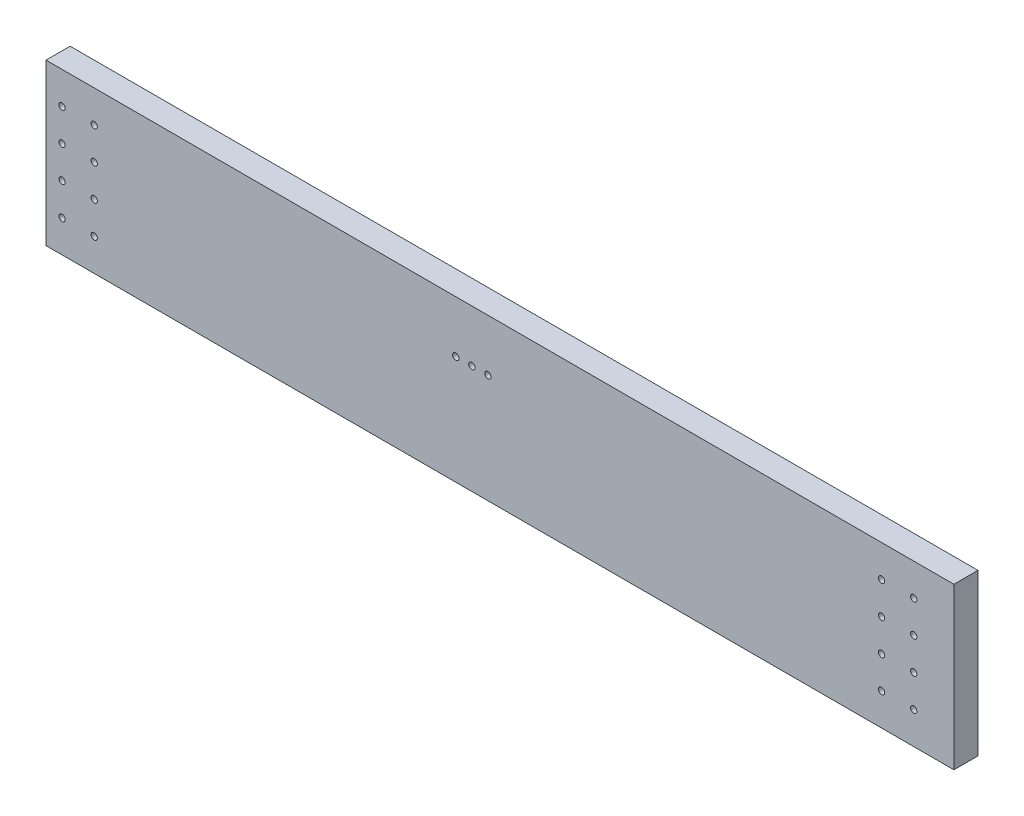
SolidWorks part; units mm, degrees
material "Pine"
ref_plane "Front Plane" through (0, 0, 0) normal (0, 0, 1) x (1, 0, 0)
ref_plane "Top Plane" through (0, 0, 0) normal (0, 1, 0) x (1, 0, 0)
ref_plane "Right Plane" through (0, 0, 0) normal (1, 0, 0) x (0, 0, -1)
sketch "Sketch1" plane through (0, 0, 0) normal (0, 0, 1) x (1, 0, 0)
  line L1 (0, 0) -> (717.55, 0)
  line L2 (0, 0) -> (0, 127)
  line L3 (0, 127) -> (717.55, 127)
  line L4 (717.55, 0) -> (717.55, 127)
  line L6 (717.55, 0) -> (717.55, 127)
  line L9 (0, 127) -> (-19.05, 127)
  line L10 (0, 127) -> (0, 0)
  line L11 (0, 0) -> (-19.05, 0)
  line L12 (-19.05, 127) -> (-19.05, 0)
  dimension "D1" = 717.55
  dimension "D2" = 127
  dimension "D3" = 19.05
extrude "Boss-Extrude1" add sketch "Sketch1" along normal blind 19.05 contours L1 L4 L3 L2
sketch "Sketch2" plane through (0, 0, 19.05) normal (0, 0, 1) x (1, 0, 0)
  line L3 (0, 0) -> (0, 127) construction
  line L4 (0, 127) -> (717.55, 127) construction
  line L5 (717.55, 0) -> (717.55, 127) construction
  circle A0 centre (12.7, 101.6) radius 2.4892
  circle A1 centre (38.1, 101.6) radius 2.4892
  circle A2 centre (38.1, 76.2) radius 2.4892
  circle A3 centre (38.1, 50.8) radius 2.4892
  circle A4 centre (38.1, 25.4) radius 2.4892
  circle A5 centre (12.7, 76.2) radius 2.4892
  circle A6 centre (12.7, 50.8) radius 2.4892
  circle A7 centre (12.7, 25.4) radius 2.4892
  circle A8 centre (685.8, 101.6) radius 2.4892
  circle A9 centre (660.4, 101.6) radius 2.4892
  circle A10 centre (660.4, 76.2) radius 2.4892
  circle A11 centre (660.4, 50.8) radius 2.4892
  circle A12 centre (660.4, 25.4) radius 2.4892
  circle A13 centre (685.8, 76.2) radius 2.4892
  circle A14 centre (685.8, 50.8) radius 2.4892
  circle A15 centre (685.8, 25.4) radius 2.4892
  dimension "D1" = 4.9784
  dimension "D2" = 25.4
  dimension "D3" = 12.7
  dimension "D6" = 25.4
  dimension "D7" = 31.75
  dimension "D8" = 4.9784
  dimension "D11" = 25.4
  dimension "D12" = 25.4
  dimension "D13" = 25.4
  dimension "D14" = 25.4
  dimension "D4" = 2
  dimension "D5" = 4
  dimension "D9" = 2
  dimension "D10" = 4
extrude "Cut-Extrude1" cut sketch "Sketch2" against normal blind 25.4
sketch "Sketch4" plane through (0, 0, 19.05) normal (0, 0, 1) x (1, 0, 0)
  line L0 (323.85, 85.979) -> (349.25, 85.979) construction
  line L1 (0, 127) -> (717.55, 127) construction
  line L2 (-19.05, 127) -> (-19.05, 0) construction
  circle A0 centre (323.85, 85.979) radius 2.4892
  circle A1 centre (336.55, 85.979) radius 2.4892
  circle A2 centre (349.25, 85.979) radius 2.4892
  dimension "D1" = 4.9784
  dimension "D2" = 41.021
  dimension "D4" = 368.3
  dimension "D3" = 12.7
extrude "Cut-Extrude2" cut sketch "Sketch4" against normal through all
